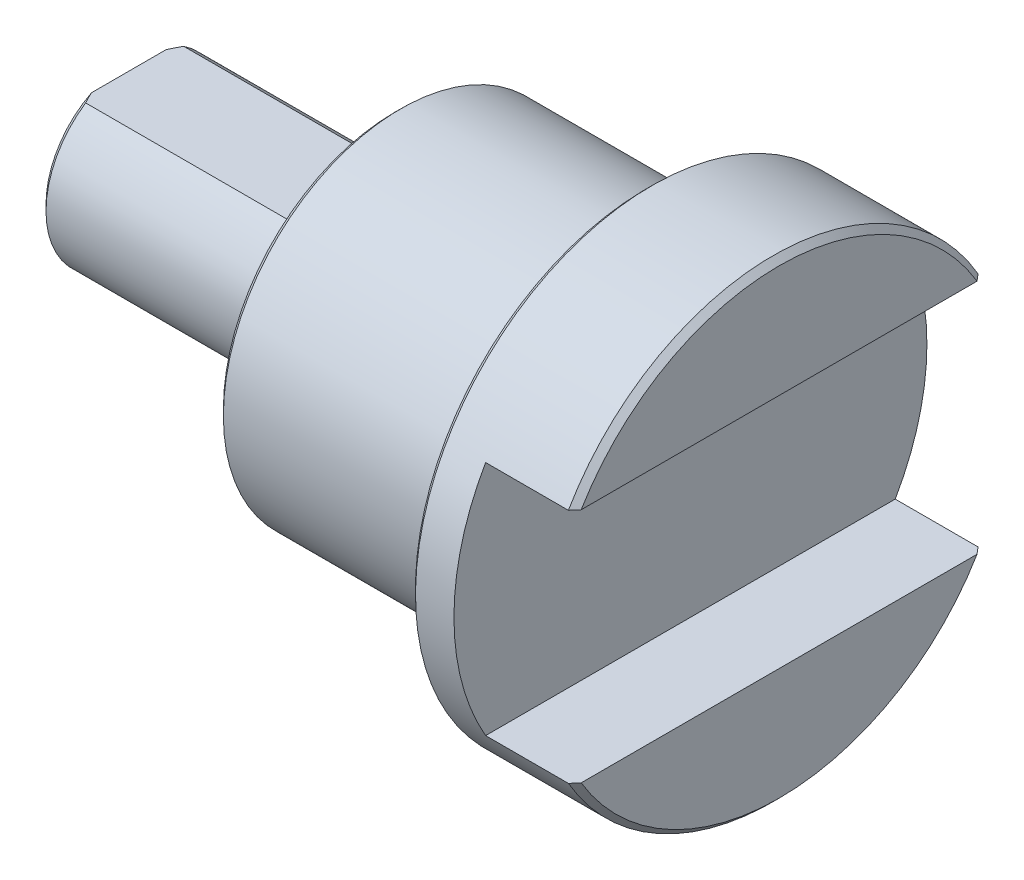
SolidWorks part; units mm, degrees
material "Alliage 6061"
ref_plane "Face" through (0, 0, 0) normal (0, 0, 1) x (1, 0, 0)
ref_plane "Dessus" through (0, 0, 0) normal (0, 1, 0) x (1, 0, 0)
ref_plane "Droite" through (0, 0, 0) normal (1, 0, 0) x (0, 0, -1)
sketch "Esquisse1" plane through (0, 0, 0) normal (0, 0, 1) x (1, 0, 0)
  line L0 (0, 0) -> (54.7909, 0) construction
  line L1 (-4.5, 6) -> (-13, 6)
  line L2 (-13, 6) -> (-13, 3)
  line L3 (-4.5, 6) -> (-4.5, 8)
  line L4 (-4.5, 8) -> (0, 8)
  line L5 (-13, 3) -> (-22, 3)
  line L6 (-22, 3) -> (-22, 0)
  line L7 (0, 0) -> (-22, 0)
  line L8 (0, 8) -> (0, 0)
  dimension "D1" = 8.5
  dimension "D2" = 9
  dimension "D3" = 12
  dimension "D4" = 6
  dimension "D6" = 16
  dimension "D7" = 4.5
revolve "Révolution1" add sketch "Esquisse1" angle 360 about L0
chamfer "Chanfrein1" distance 0.2 angle 45 4 edges at (0, 0, 8) (-4.5, 0, 8) (-13, 0, 6) (-22, 0, 3)
sketch "Esquisse2" plane through (0, 0, 0) normal (0, 1, 0) x (1, 0, 0)
  line L0 (0, -7.8) -> (0, 7.8) construction
  line L1 (0, 4) -> (-3, 4)
  line L2 (0, 4) -> (0, -4)
  line L3 (0, -4) -> (-3, -4)
  line L4 (-3, 4) -> (-3, -4)
  dimension "D1" = 4
  dimension "D2" = 8
  dimension "D3" = 3
extrude "Enlèv. mat.-Extru.1" [suppressed] cut sketch "Esquisse2" against normal mid plane 20
sketch "Esquisse3" plane through (-22, 0, 0) normal (-1, 0, 0) x (0, 0, 1)
  line L1 (-4, 4.5) -> (4, 4.5)
  line L2 (-4, 4.5) -> (-4, 2.5)
  line L3 (-4, 2.5) -> (4, 2.5)
  line L4 (4, 4.5) -> (4, 2.5)
  dimension "D1" = 2.5
extrude "Enlèv. mat.-Extru.2" cut sketch "Esquisse3" against normal blind 8
sketch "Esquisse4" plane through (0, 0, 0) normal (0, 0, 1) x (1, 0, 0)
  line L0 (0, -7.8) -> (0, 7.8) construction
  line L1 (0, 4) -> (-3, 4)
  line L2 (0, 4) -> (0, -4)
  line L3 (0, -4) -> (-3, -4)
  line L4 (-3, 4) -> (-3, -4)
  dimension "D1" = 4
  dimension "D2" = 8
  dimension "D3" = 3
extrude "Enlèv. mat.-Extru.3" cut sketch "Esquisse4" against normal mid plane 20
